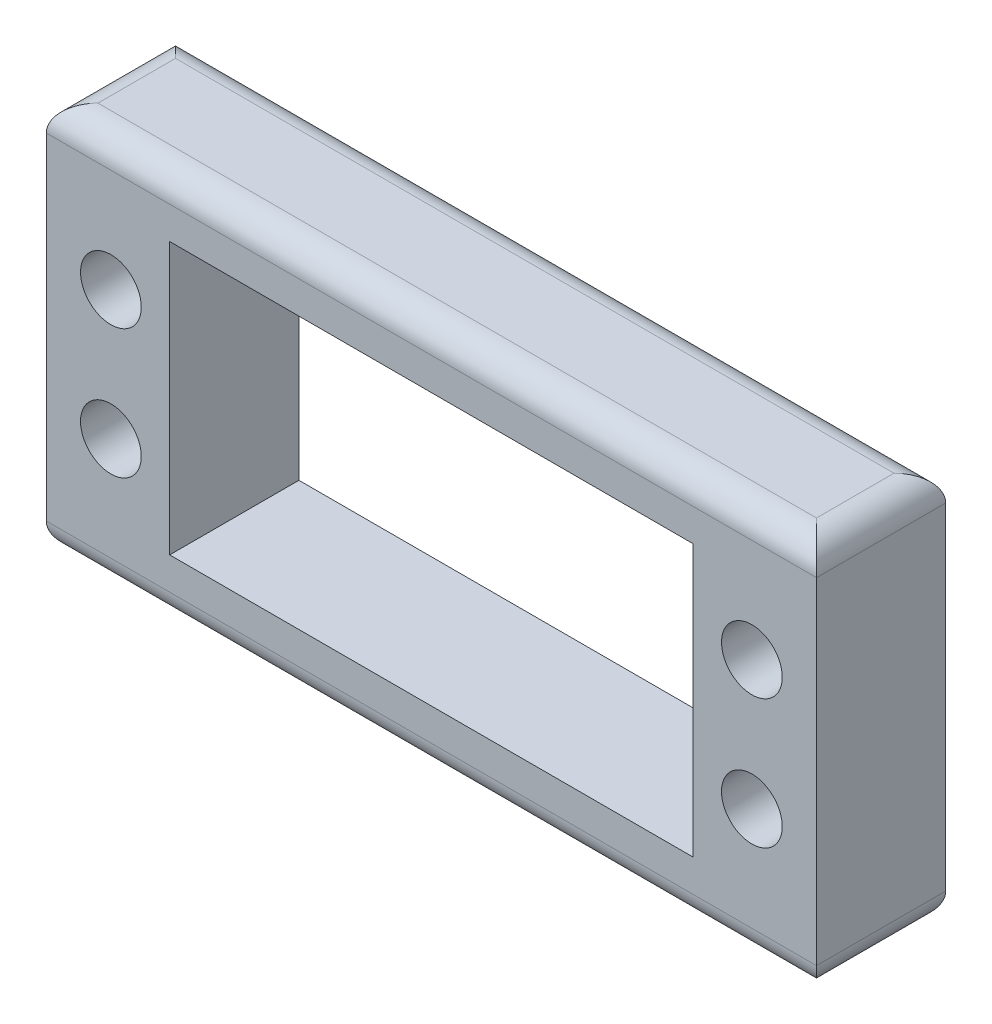
SolidWorks part; units mm, degrees
ref_plane "Front Plane" through (0, 0, 0) normal (0, 0, 1) x (1, 0, 0)
ref_plane "Top Plane" through (0, 0, 0) normal (0, 1, 0) x (1, 0, 0)
ref_plane "Right Plane" through (0, 0, 0) normal (1, 0, 0) x (0, 0, -1)
sketch "Sketch1" plane through (0, 0, 0) normal (0, 0, 1) x (1, 0, 0)
  line L0 (29.8, 15) -> (29.8, -15)
  line L1 (-29.8, 15) -> (29.8, 15)
  line L2 (-29.8, 15) -> (-29.8, -15)
  line L4 (-24.8, 5) -> (-24.8, -5) construction
  line L5 (-24.8, 5) -> (24.8, 5) construction
  line L6 (-20.25, 10.5) -> (20.25, 10.5)
  line L7 (-20.25, 10.5) -> (-20.25, -10.5)
  line L8 (-20.25, -10.5) -> (20.25, -10.5)
  line L9 (20.25, 10.5) -> (20.25, -10.5)
  line L10 (-20.25, 10.5) -> (20.25, -10.5) construction
  line L11 (-20.25, -10.5) -> (20.25, 10.5) construction
  line L12 (-29.8, -15) -> (29.8, -15)
  circle A1 centre (-24.8, 5) radius 2.35
  circle A2 centre (24.8, 5) radius 2.35
  circle A3 centre (24.8, -5) radius 2.35
  circle A4 centre (-24.8, -5) radius 2.35
  point P0 (-24.8, -5)
  point P5 (0, -15)
  point P8 (-29.8, 0)
  point P9 (-24.8, 0)
  point P16 (0, 0)
  point P24 (0, 5)
  dimension "D4" = 4.7
  dimension "D5" = 49.6
  dimension "D7" = 10
  dimension "D2" = 30
  dimension "D6" = 5
  dimension "D8" = 40.5
  dimension "D9" = 21
extrude "Boss-Extrude1" add sketch "Sketch1" along normal blind 10
fillet "Fillet1" radius 2 8 edges at (0, 15, 10) (0, 15, 0) (-29.8, -15, 5) (0, -15, 10) (0, -15, 0) (29.8, -15, 5) (29.8, 15, 5) (-29.8, 15, 5)
